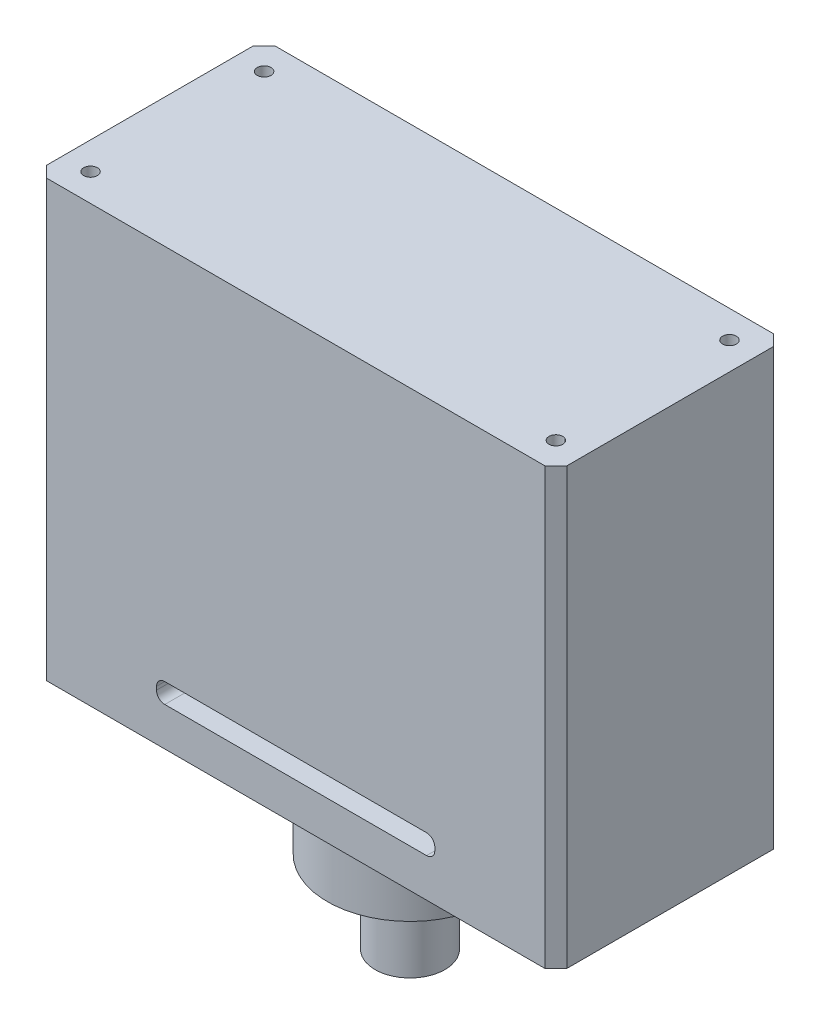
SolidWorks part; units mm, degrees
ref_plane "Front Plane" through (0, 0, 0) normal (0, 0, 1) x (1, 0, 0)
ref_plane "Top Plane" through (0, 0, 0) normal (0, 1, 0) x (1, 0, 0)
ref_plane "Right Plane" through (0, 0, 0) normal (1, 0, 0) x (0, 0, -1)
sketch "Sketch1" plane through (0, 0, 0) normal (0, 1, 0) x (1, 0, 0)
  line L0 (0, 39.5) -> (2, 41.5)
  line L1 (2, 0) -> (92.45, 0)
  line L2 (0, 2) -> (0, 39.5)
  line L3 (2, 41.5) -> (92.45, 41.5)
  line L4 (94.45, 2) -> (94.45, 39.5)
  line L5 (94.45, 39.5) -> (92.45, 41.5)
  line L6 (92.45, 0) -> (94.45, 2)
  line L7 (2, 0) -> (0, 2)
  point P0 (0, 0)
  point P1 (94.45, 41.5)
  point P2 (0, 41.5)
  point P3 (94.45, 0)
  dimension "D1" = 41.5
  dimension "D2" = 94.45
extrude "Boss-Extrude1" add sketch "Sketch1" along normal blind 79
sketch "Sketch2" plane through (0, 0, -41.5) normal (0, 0, -1) x (-1, 0, 0)
  line L1 (-6.284, 3.4465) -> (-18.984, 3.4465)
  line L2 (-6.284, 3.4465) -> (-6.284, 22.4965)
  line L3 (-6.284, 22.4965) -> (-18.984, 22.4965)
  line L4 (-18.984, 3.4465) -> (-18.984, 22.4965)
  dimension "D1" = 19.05
  dimension "D2" = 12.7
extrude "Boss-Extrude2" add sketch "Sketch2" along normal blind 2.7
pattern_linear "LPattern1" count 2 spacing 70 along (1, 0, 0) count 2 spacing 52 along (0, 1, 0) of "Boss-Extrude2"
sketch "Sketch3" plane through (0, 0, 0) normal (0, -1, 0) x (1, 0, 0)
  line L0 (2, 0) -> (92.45, 0) construction
  circle A0 centre (47.225, -20.75) radius 15
  point P4 (47.225, 0)
  dimension "D1" = 30
  dimension "D2" = 0
extrude "Boss-Extrude3" add sketch "Sketch3" along normal blind 15
sketch "Sketch4" plane through (0, -15, 0) normal (0, -1, 0) x (1, 0, 0)
  circle A0 centre (47.225, -20.75) radius 6.35
  dimension "D1" = 12.7
extrude "Boss-Extrude4" add sketch "Sketch4" along normal blind 15
sketch "Sketch5" plane through (0, 0, 0) normal (0, 0, 1) x (1, 0, 0)
  line L0 (2, 0) -> (92.45, 0) construction
  line L1 (70.975, 7) -> (23.475, 7)
  line L2 (72.475, 8.5) -> (72.475, 9.1)
  line L3 (70.975, 10.6) -> (23.475, 10.6)
  line L4 (21.975, 8.5) -> (21.975, 9.1)
  line L5 (72.475, 7) -> (21.975, 10.6) construction
  line L6 (72.475, 10.6) -> (21.975, 7) construction
  arc A0 (72.475, 8.5) -> (70.975, 7) centre (70.975, 8.5) cw
  arc A1 (72.475, 9.1) -> (70.975, 10.6) centre (70.975, 9.1) ccw
  arc A2 (21.975, 8.5) -> (23.475, 7) centre (23.475, 8.5) ccw
  arc A3 (21.975, 9.1) -> (23.475, 10.6) centre (23.475, 9.1) cw
  point P0 (47.225, 8.8)
  point P7 (47.225, 0)
  dimension "D5" = 1.5
  dimension "D1" = 50.5
  dimension "D2" = 3.6
  dimension "D3" = 7
  dimension "D4" = 0
extrude "Cut-Extrude1" cut sketch "Sketch5" against normal through all
sketch "Sketch6" plane through (0, 0, 0) normal (0, -1, 0) x (1, 0, 0)
  line L0 (2, 0) -> (92.45, 0) construction
  line L1 (0, -39.5) -> (0, -2) construction
  line L2 (94.45, -2) -> (94.45, -39.5) construction
  line L3 (92.45, -41.5) -> (2, -41.5) construction
  point P0 (5, -5)
  point P1 (89.45, -36.5)
  point P10 (89.45, -5)
  point P11 (5, -36.5)
  dimension "D1" = 5
  dimension "D2" = 5
  dimension "D3" = 5
  dimension "D4" = 5
  dimension "D5" = 0
hole_wizard "Tap Drill for M3x0.5 Tap1" positions "Sketch7" profile "Sketch8" hole size "M3x0.5" standard "ANSI Metric" end condition through all
sketch "Sketch7" plane through (0, 0, 0) normal (0, -1, 0) x (-1, 0, 0)
  point P0 (-5, 5)
  point P3 (-5, 36.5)
  point P6 (-89.45, 36.5)
  point P9 (-89.45, 5)
sketch "Sketch8" plane through (5, 0, -5) normal (1, 0, 0) x (0, 0, -1)
  line L0 (0, 0) -> (0, 79)
  line L1 (0, 79) -> (1.25, 79)
  line L2 (1.25, 79) -> (1.25, 0)
  line L5 (1.25, 0) -> (0, 0)
  line L11 (0, -6.35) -> (0, 107.95) construction
  dimension "Thru Hole Dia." = 2.5
  dimension "Thru Hole Depth" = 79
